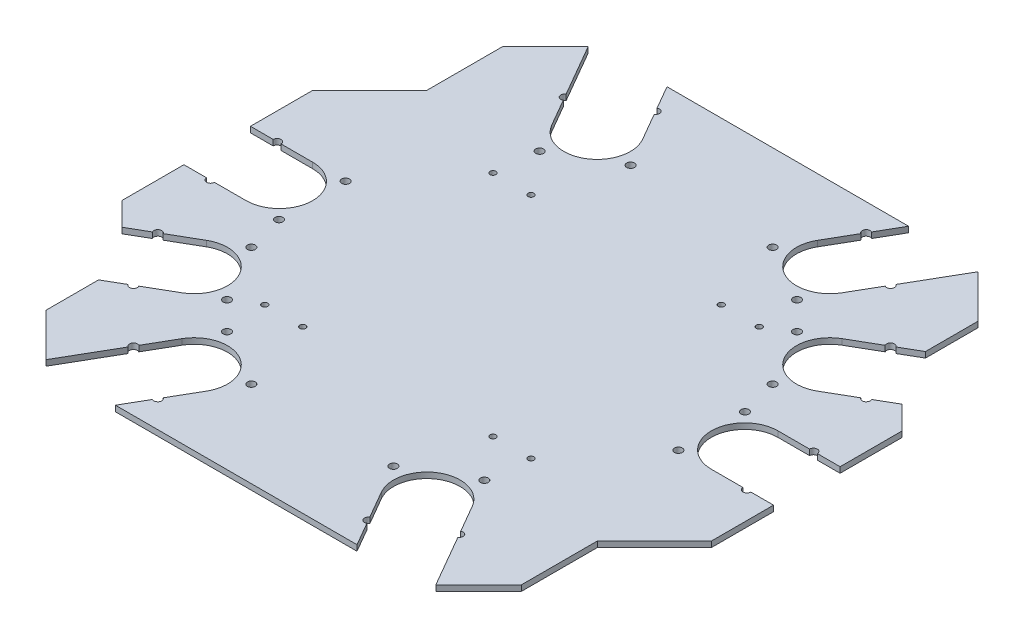
SolidWorks part; units mm, degrees
material "CF-ntbk"
ref_plane "Front Plane" through (0, 0, 0) normal (0, 0, 1) x (1, 0, 0)
ref_plane "Top Plane" through (0, 0, 0) normal (0, 1, 0) x (1, 0, 0)
ref_plane "Right Plane" through (0, 0, 0) normal (1, 0, 0) x (0, 0, -1)
sketch "Sketch1" plane through (0, 0, 0) normal (0, 1, 0) x (1, 0, 0)
  line L0 (-100, 145) -> (-125, 120)
  line L1 (-125, 120) -> (-125, 80)
  line L2 (-125, 80) -> (-155, 50)
  line L3 (-155, 50) -> (-155, -50)
  line L4 (-155, -50) -> (-125, -80)
  line L5 (-125, -80) -> (-125, -120)
  line L6 (-125, -120) -> (-100, -145)
  line L7 (-100, -145) -> (100, -145)
  line L8 (100, -145) -> (125, -120)
  line L9 (125, -120) -> (125, -80)
  line L10 (125, -80) -> (155, -50)
  line L11 (155, -50) -> (155, 50)
  line L12 (155, 50) -> (125, 80)
  line L13 (125, 80) -> (125, 120)
  line L14 (125, 120) -> (100, 145)
  line L15 (100, 145) -> (-100, 145)
  line L17 (-44.2539, 0) -> (44.2539, 0) construction
  line L18 (0, -44.7868) -> (0, 44.7868) construction
  dimension "D2" = 145
  dimension "D1" = 100
  dimension "D3" = 290
  dimension "D4" = 200
  dimension "D5" = 100
  dimension "D6" = 30
  dimension "D7" = 40
  dimension "D8" = 135
extrude "Boss-Extrude1" add sketch "Sketch1" along normal blind 3
sketch "Sketch2" plane through (0, 3, 0) normal (0, 1, 0) x (1, 0, 0)
  line L0 (-79.7985, -138.215) -> (79.7985, 138.215) construction
  line L1 (46.2229, 94.5567) -> (65.2799, 83.5542) construction
  line L2 (-69.8318, 120.9522) -> (69.8318, -120.9522) construction
  line L3 (0, -44.7868) -> (0, 44.7868) construction
  line L5 (-44.2539, 0) -> (44.2539, 0) construction
  line L6 (-150.8166, 0) -> (150.8166, 0) construction
  line L7 (-118.217, -118.217) -> (118.217, 118.217) construction
  line L8 (-102.6144, 102.6144) -> (102.6144, -102.6144) construction
  line L9 (105, 17.5) -> (105, -8.6918) construction
  line L11 (48.1946, -93.4184) -> (56.6973, -88.5094) construction
  circle A0 centre (55.3446, 130.8596) radius 2.05
  circle A1 centre (37.3446, 99.6827) radius 2.05
  circle A2 centre (37.3446, -99.6827) radius 2.05
  circle A3 centre (55.3446, -130.8596) radius 2.05
  circle A4 centre (105, 17.5) radius 2.05
  circle A5 centre (141, 17.5) radius 2.05
  circle A12 centre (105, -17.5) radius 2.05
  circle A13 centre (141, -17.5) radius 2.05
  circle A16 centre (85.6554, -113.3596) radius 2.05
  circle A17 centre (67.6554, -82.1827) radius 2.05
  circle A18 centre (85.6554, 113.3596) radius 2.05
  circle A19 centre (67.6554, 82.1827) radius 2.05
  dimension "D1" = 4.1
  dimension "D2" = 36
  dimension "D3" = 30
  dimension "D5" = 30
  dimension "D6" = 36
  dimension "D8" = 36
  dimension "D10" = 45
  dimension "D11" = 45
  dimension "D4" = 17.5
  dimension "D7" = 105
  dimension "D9" = 17.5
  dimension "D15" = 105
  dimension "D17" = 105
  dimension "D20" = 17.5
  dimension "D21" = 17.5
  dimension "D24" = 17.5
  dimension "D25" = 17.5
  dimension "D29" = 17.5
  dimension "D30" = 17.5
  dimension "D31" = 36
  dimension "D12" = 17.5
  dimension "D13" = 17.5
  dimension "D14" = 36
  dimension "D16" = 17.5
  dimension "D18" = 17.5
  dimension "D19" = 36
extrude "HexCut1" cut sketch "Sketch2" against normal up to surface (3 mm away) up to face at (0, 0, 0)
mirror "HexCut2" about plane through (0, 0, 0) normal (1, 0, 0) of "HexCut1"
sketch "ConstructLines" plane through (0, 3, 0) normal (0, 1, 0) x (1, 0, 0)
  line L0 (0, 121.6855) -> (0, -121.6855) construction
  line L1 (-91.1915, 0) -> (91.1915, 0) construction
  line L2 (-44.2539, 0) -> (44.2539, 0) construction
  line L3 (-70.8661, 122.7437) -> (70.8661, -122.7437) construction
  line L4 (-122.7437, -70.8661) -> (122.7437, 70.8661) construction
  dimension "D1" = 30
ref_point "Point1"
sketch "Sketch5" plane through (0, 3, 0) normal (0, 1, 0) x (1, 0, 0)
  line L0 (0, 121.6855) -> (0, -121.6855) construction
  line L1 (-91.1915, 0) -> (91.1915, 0) construction
  circle A0 centre (50, 60) radius 1.55
  circle A1 centre (70, 60) radius 1.55
  dimension "D1" = 3.1
  dimension "D2" = 20
  dimension "D3" = 50
  dimension "D4" = 60
  dimension "D5" = 60
extrude "Cut-Extrude2" cut sketch "Sketch5" against normal up to surface (3 mm away) up to face at (-55.3446, 0, -128.8096)
pattern_linear "LPattern1" count 2 spacing 120 along (0, 0, 1) count 2 spacing 120 along (-1, 0, 0) of "Cut-Extrude2"
sketch "Sketch6" plane through (0, 3, 0) normal (0, 1, 0) x (1, 0, 0)
  line L0 (-126.2708, -72.9025) -> (126.2708, 72.9025) construction
  line L1 (0, 121.6855) -> (0, -121.6855) construction
  line L2 (87.7927, 57.9385) -> (95.9037, 43.89) construction
  line L3 (-69.5169, 120.4068) -> (69.5169, -120.4068) construction
  circle A0 centre (99.6827, 37.3446) radius 2.05
  circle A1 centre (130.8596, 55.3446) radius 2.05
  circle A2 centre (113.3596, 85.6554) radius 2.05
  circle A3 centre (82.1827, 67.6554) radius 2.05
  dimension "D4" = 4.1
  dimension "D1" = 60
  dimension "D2" = 105
  dimension "D3" = 36
  dimension "D5" = 17.5
  dimension "D6" = 17.5
  dimension "D7" = 17.5
  dimension "D8" = 17.5
  dimension "D9" = 36
  dimension "D17" = 30
extrude "QuadCut1" cut sketch "Sketch6" against normal up to surface (3 mm away) up to face at (70, 0, 61.55)
ref_plane "MirrorPlaneQuad" through (0, 0, 0) normal (0.866, 0, -0.5) x (-0.5, 0, -0.866)
mirror "Mirror1" about plane through (0, 0, 0) normal (0.866, 0, -0.5) of "QuadCut1"
sketch "Sketch7" plane through (0, 3, 0) normal (0, 1, 0) x (1, 0, 0)
  line L0 (45.9946, 114.6649) -> (83.4946, 179.6168)
  line L1 (83.4946, 179.6168) -> (113.8054, 162.1168)
  line L2 (113.8054, 162.1168) -> (76.3054, 97.1649)
  line L3 (37.3446, 99.6827) -> (67.6554, 82.1827) construction
  line L4 (105, 17.5) -> (105, -17.5) construction
  line L5 (37.3446, -99.6827) -> (67.6554, -82.1827) construction
  line L6 (45.9946, -114.6649) -> (83.4946, -179.6168)
  line L7 (76.3054, -97.1649) -> (113.8054, -162.1168)
  line L8 (83.4946, -179.6168) -> (113.8054, -162.1168)
  line L9 (122.3, 17.5) -> (162.3, 17.5)
  line L10 (162.3, 17.5) -> (162.3, -17.5)
  line L11 (162.3, -17.5) -> (122.3, -17.5)
  arc A0 (45.9946, 114.6649) -> (76.3054, 97.1649) centre (61.15, 105.9149) ccw
  circle A1 centre (85.6554, -113.3596) radius 2.05 construction
  arc A2 (122.3, 17.5) -> (122.3, -17.5) centre (122.3, 0) ccw
  circle A3 centre (55.3446, 130.8596) radius 2.05 construction
  circle A4 centre (85.6554, 113.3596) radius 2.05 construction
  arc A6 (76.3054, -97.1649) -> (45.9946, -114.6649) centre (61.15, -105.9149) ccw
  circle A7 centre (55.3446, -130.8596) radius 2.05 construction
  dimension "D1" = 0
  dimension "D3" = 0
  dimension "D4" = 35
  dimension "D6" = 35
  dimension "D7" = 0
  dimension "D12" = 0
  dimension "D2" = 75
  dimension "D5" = 17.3
  dimension "D8" = 75
  dimension "D9" = 17.3
  dimension "D10" = 17.3
  dimension "D11" = 40
extrude "Cut-Extrude3" cut sketch "Sketch7" against normal up to surface (3 mm away) up to face at (-82.1827, 0, 69.7054)
mirror "Mirror2" about plane through (0, 0, 0) normal (1, 0, 0) of "Cut-Extrude3"
sketch "Sketch8" plane through (0, 3, 0) normal (0, 1, 0) x (1, 0, 0)
  line L0 (82.1827, 67.6554) -> (99.6827, 37.3446) construction
  line L1 (97.1649, 76.3054) -> (131.8059, 96.3054)
  line L2 (131.8059, 96.3054) -> (149.3059, 65.9946)
  line L3 (149.3059, 65.9946) -> (114.6649, 45.9946)
  arc A0 (97.1649, 76.3054) -> (114.6649, 45.9946) centre (105.9149, 61.15) ccw
  circle A1 centre (130.8596, 55.3446) radius 2.05 construction
  circle A2 centre (113.3596, 85.6554) radius 2.05 construction
  dimension "D1" = 35
  dimension "D2" = 17.3
  dimension "D3" = 40
  dimension "D4" = 0
  dimension "D5" = 0
extrude "Cut-Extrude4" cut sketch "Sketch8" against normal up to surface (3 mm away) up to face at (0, 0, 0)
mirror "Mirror3" about plane through (0, 0, 0) normal (0.866, 0, -0.5) of "Cut-Extrude4"
equation "\"ClampHoleDist\"= 36"
equation "\"D2@Sketch2\"=\"ClampHoleDist\""
equation "\"ClampDistMid\"=105"
equation "\"Length\"= 290"
equation "\"D3@Sketch1\"=\"Length\""
equation "\"Width\"= 200"
equation "\"D1@Sketch1\"=\"Width\"/2"
equation "\"D2@Sketch1\"=\"Length\"/2"
equation "\"D4@Sketch1\"=\"Width\""
equation "\"D7@Sketch1\"=(\"Length\"- 210)/2"
equation "\"D8@Sketch2\"=\"ClampHoleDist\""
equation "\"D6@Sketch2\"=\"ClampHoleDist\""
equation "\"HoleZDist\"=60.000000"
equation "\"D5@Sketch5\"=\"HoleZDist\""
equation "\"D4@Sketch5\"=\"HoleZDist\""
equation "\"HoleXDist\"=50.000000"
equation "\"D3@Sketch5\"=\"HoleXDist\""
equation "\"HoleSpacing\"=20"
equation "\"D2@Sketch5\"=\"HoleSpacing\""
equation "\"D3@LPattern1\"=\"HoleZDist\"*2"
equation "\"D4@LPattern1\"=\"HoleXDist\"*2+(\"HoleSpacing\")"
equation "\"ClampHoriDist\"=17.5"
equation "\"D4@Sketch2\"=\"ClampHoriDist\""
equation "\"D9@Sketch2\"=\"ClampHoriDist\""
equation "\"D7@Sketch2\"=\"ClampDistMid\""
equation "\"D15@Sketch2\"=\"ClampDistMid\""
equation "\"D17@Sketch2\"=\"ClampDistMid\""
equation "\"D20@Sketch2\"=\"ClampHoriDist\""
equation "\"D21@Sketch2\"=\"ClampHoriDist\""
equation "\"D24@Sketch2\"=\"ClampHoriDist\""
equation "\"D25@Sketch2\"=\"ClampHoriDist\""
equation "\"D29@Sketch2\"=\"ClampHoriDist\""
equation "\"D30@Sketch2\"=\"ClampHoriDist\""
equation "\"D31@Sketch2\"=\"ClampHoleDist\""
equation "\"D12@Sketch2\"=\"ClampHoriDist\""
equation "\"D13@Sketch2\"=\"ClampHoriDist\""
equation "\"D14@Sketch2\"=\"ClampHoleDist\""
equation "\"ClampHoleSize\"=4.1"
equation "\"D1@Sketch2\"=\"ClampHoleSize\""
equation "\"D16@Sketch2\"=\"ClampHoriDist\""
equation "\"D19@Sketch2\"=\"ClampHoleDist\""
equation "\"D18@Sketch2\"=\"ClampHoriDist\""
equation "\"D2@Sketch6\"=\"ClampDistMid\""
equation "\"D3@Sketch6\"=\"ClampHoleDist\""
equation "\"D4@Sketch6\"=\"ClampHoleSize\""
equation "\"D5@Sketch6\"=\"ClampHoriDist\""
equation "\"D6@Sketch6\"=\"ClampHoriDist\""
equation "\"D7@Sketch6\"=\"ClampHoriDist\""
equation "\"D8@Sketch6\"=\"ClampHoriDist\""
equation "\"D9@Sketch6\"=\"ClampHoleDist\""
equation "\"TubeOutDiam\"= 25.1"
equation "\"D1@Sketch8\"=\"TubeOutDiam\"+ 9.9"
